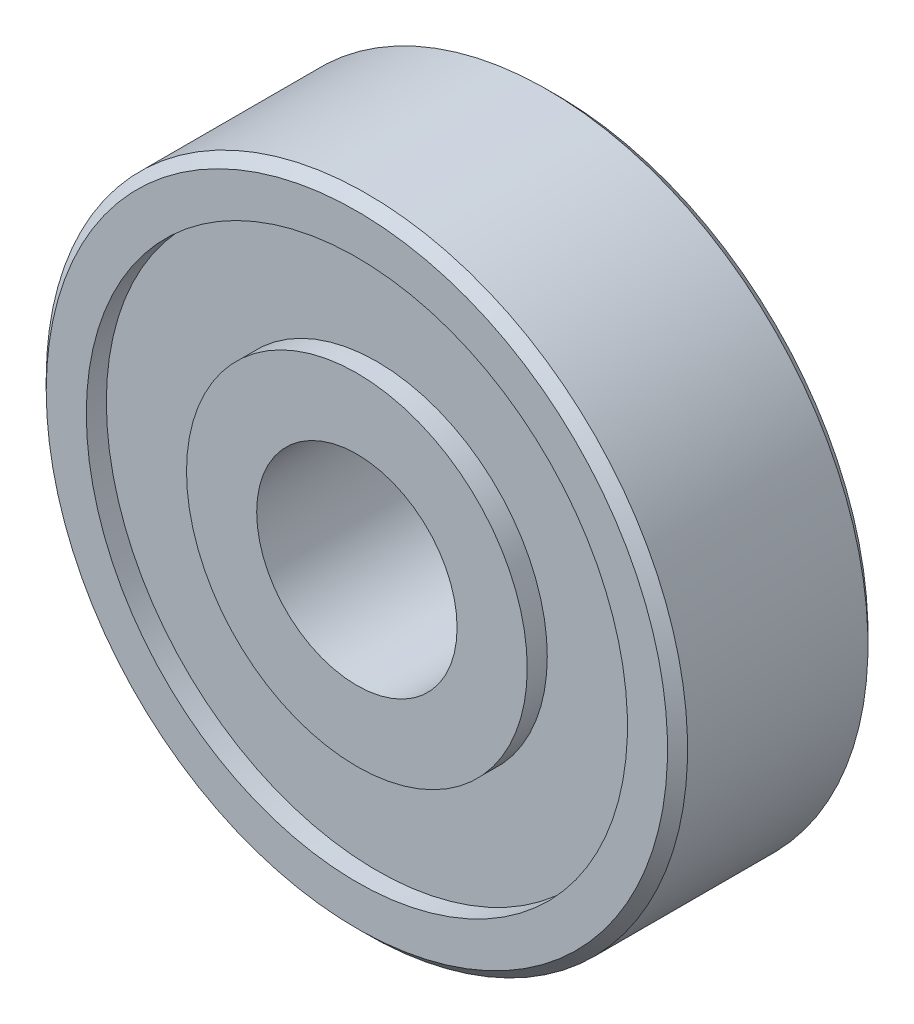
SolidWorks part; units mm, degrees
ref_plane "Front Plane" through (0, 0, 0) normal (0, 0, 1) x (1, 0, 0)
ref_plane "Top Plane" through (0, 0, 0) normal (0, 1, 0) x (1, 0, 0)
ref_plane "Right Plane" through (0, 0, 0) normal (1, 0, 0) x (0, 0, -1)
ref_plane "Plane1" through (0, 0, 0) normal (0, -1, 0) x (1, 0, 0)
sketch "Sketch1" plane through (0, 0, 0) normal (0, -1, 0) x (1, 0, 0)
  line L0 (6.5, 2.25) -> (6.25, 2.5)
  line L1 (6.25, 2.5) -> (5.25, 2.5)
  line L2 (5.25, 2.5) -> (5.25, 2)
  line L3 (5.25, 2) -> (2.75, 2)
  line L4 (2.75, 2) -> (2.75, 2.5)
  line L5 (2.75, 2.5) -> (1, 2.5)
  line L6 (1, 2.5) -> (1, -2.5)
  line L7 (1, -2.5) -> (2.75, -2.5)
  line L8 (2.75, -2.5) -> (2.75, -2)
  line L9 (2.75, -2) -> (5.25, -2)
  line L10 (5.25, -2) -> (5.25, -2.5)
  line L11 (5.25, -2.5) -> (6.25, -2.5)
  line L12 (6.25, -2.5) -> (6.5, -2.25)
  line L13 (6.5, -2.25) -> (6.5, 2.25)
  line L14 (-1.5, 2.5) -> (-1.5, -2.5) construction
  dimension "D1" = 16
  dimension "D2" = 5
  dimension "D3" = 13.5
  dimension "D4" = 8.5
  dimension "D5" = 5
  dimension "D6" = 0.5
  dimension "D7" = 0.5
revolve "Revolve1" add sketch "Sketch1" angle 360 about L14
